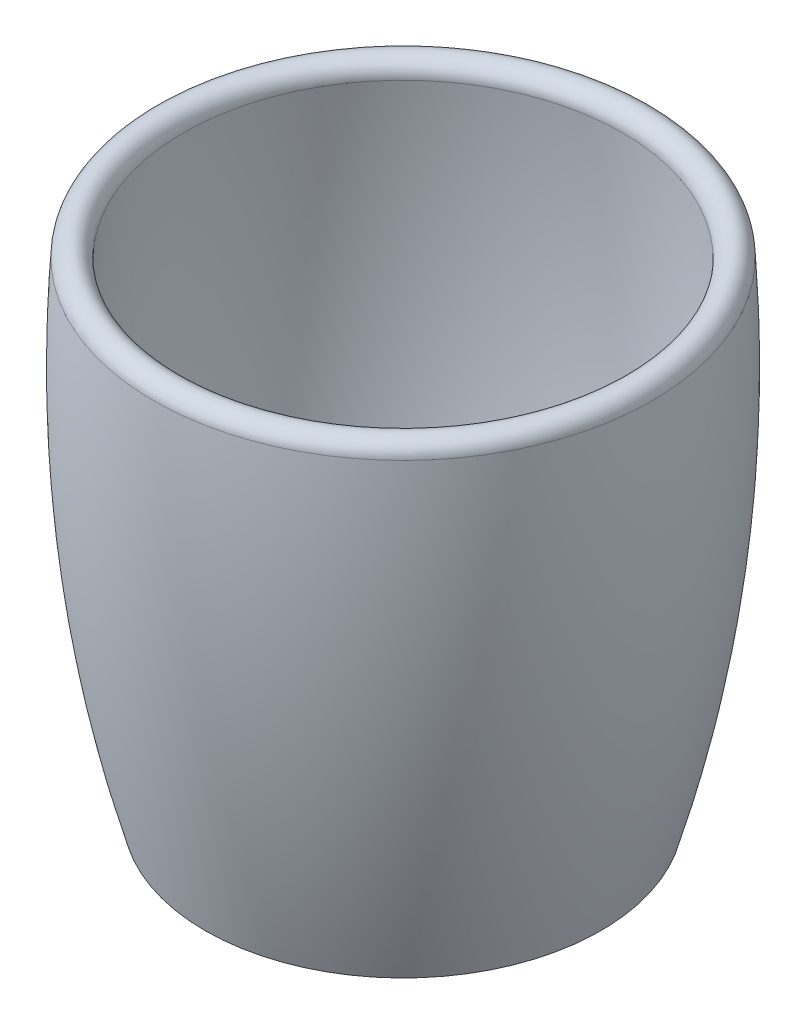
SolidWorks part; units mm, degrees
ref_plane "Front Plane" through (0, 0, 0) normal (0, 0, 1) x (1, 0, 0)
ref_plane "Top Plane" through (0, 0, 0) normal (0, 1, 0) x (1, 0, 0)
ref_plane "Right Plane" through (0, 0, 0) normal (1, 0, 0) x (0, 0, -1)
sketch "Sketch1" plane through (0, 0, 0) normal (0, 0, 1) x (1, 0, 0)
  line L0 (0, 0) -> (33.25, 0)
  line L1 (0, 0) -> (0, 95.7413) construction
  line L2 (40, 95.7413) -> (40, -12.04) construction
  line L3 (55.8118, 78.6822) -> (10.6882, -78.6822) construction
  line L4 (0, 5) -> (29.4504, 5)
  line L5 (0, 0) -> (0, 5)
  arc A0 (41.85, 81.4) -> (36.8601, 81.0819) centre (39.3551, 81.241) ccw
  spline S0 degree 3 poles (33.25, 0) (40.7706, 26.2274) (43.6373, 53.3607) (41.85, 81.4) knots 0 0 0 0 1 1 1 1
  spline S1 degree 1 poles (29.4504, 5) (36.8601, 81.0819) knots 0 0 1 1 construction
  spline S2 degree 3 poles (29.4504, 5) (31.0987, 11.1227) (33.8901, 23.5135) (36.5163, 42.3627) (37.4144, 58.3464) (37.3573, 71.2745) (37.0678, 77.8233) (36.8601, 81.0819) knots 0.046951 0.046951 0.046951 0.046951 0.285214 0.523476 0.761738 0.880869 1 1 1 1
  point P4 (40.0818, 32.2)
  point P14 (0, 0)
  dimension "D1" = 81.4
  dimension "D2" = 83.7
  dimension "D3" = 66.5
  dimension "D4" = 32.2
  dimension "D5" = 40
  dimension "D6" = 74
  dimension "D8" = 81.241
  dimension "D7" = 5
revolve "Revolve1" add sketch "Sketch1" angle 360 about L1
